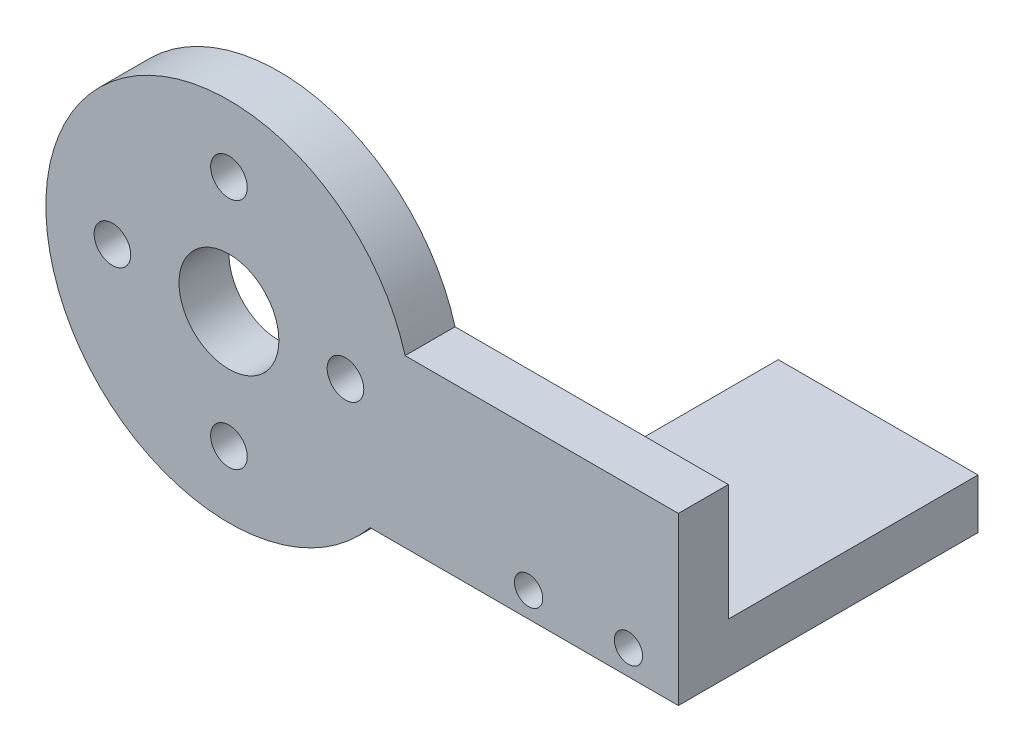
SolidWorks part; units mm, degrees
ref_plane "Front Plane" through (0, 0, 0) normal (0, 0, 1) x (1, 0, 0)
ref_plane "Top Plane" through (0, 0, 0) normal (0, 1, 0) x (1, 0, 0)
ref_plane "Right Plane" through (0, 0, 0) normal (1, 0, 0) x (0, 0, -1)
sketch "Stock_horn_attachment_profile" plane through (0, 0, 0) normal (0, 0, 1) x (1, 0, 0)
  circle A0 centre (0, 0) radius 11
  dimension "D1" = 22
extrude "Stock_horn_attachment" add sketch "Stock_horn_attachment_profile" along normal blind 3 from offset 15
sketch "Finger_arm_profile" plane through (0, 0, 0) normal (0, 0, 1) x (1, 0, 0)
  line L1 (0, -7) -> (27, -7)
  line L2 (0, -7) -> (0, 3)
  line L3 (0, 3) -> (27, 3)
  line L4 (27, -7) -> (27, 3)
  dimension "D1" = 27
  dimension "D2" = 10
extrude "Finger_arm" add sketch "Finger_arm_profile" along normal blind 3 from offset 15
sketch "Descending_contact_finger_profile" plane through (0, 0, 0) normal (0, 0, 1) x (1, 0, 0)
  line L1 (15, -7) -> (27, -7)
  line L2 (15, -7) -> (15, -4)
  line L3 (15, -4) -> (27, -4)
  line L4 (27, -7) -> (27, -4)
  dimension "D1" = 12
  dimension "D2" = 3
extrude "Descending_contact_finger" add sketch "Descending_contact_finger_profile" along normal blind 18
sketch "Horn_center_access_profile" plane through (0, 0, 0) normal (0, 0, 1) x (1, 0, 0)
  circle A0 centre (0, 0) radius 3
  dimension "D1" = 6
extrude "Horn_center_access" cut sketch "Horn_center_access_profile" along normal through all from offset 50
sketch "Horn_screws_profile" plane through (0, 0, 0) normal (0, 0, 1) x (1, 0, 0)
  circle A0 centre (0, -7) radius 1.1
  circle A1 centre (0, 7) radius 1.1
  circle A2 centre (-7, 0) radius 1.1
  circle A3 centre (7, 0) radius 1.1
  dimension "D1" = 2.2
  dimension "D2" = 2.2
  dimension "D3" = 2.2
  dimension "D4" = 2.2
extrude "Horn_screws" cut sketch "Horn_screws_profile" along normal through all from offset 50
sketch "Contact_pad_keeper_profile" plane through (0, 0, 0) normal (0, 0, 1) x (1, 0, 0)
  circle A0 centre (18, -5.5) radius 0.85
  circle A1 centre (24, -5.5) radius 0.85
  dimension "D1" = 1.7
  dimension "D2" = 1.7
extrude "Contact_pad_keeper" cut sketch "Contact_pad_keeper_profile" along normal through all from offset 50
